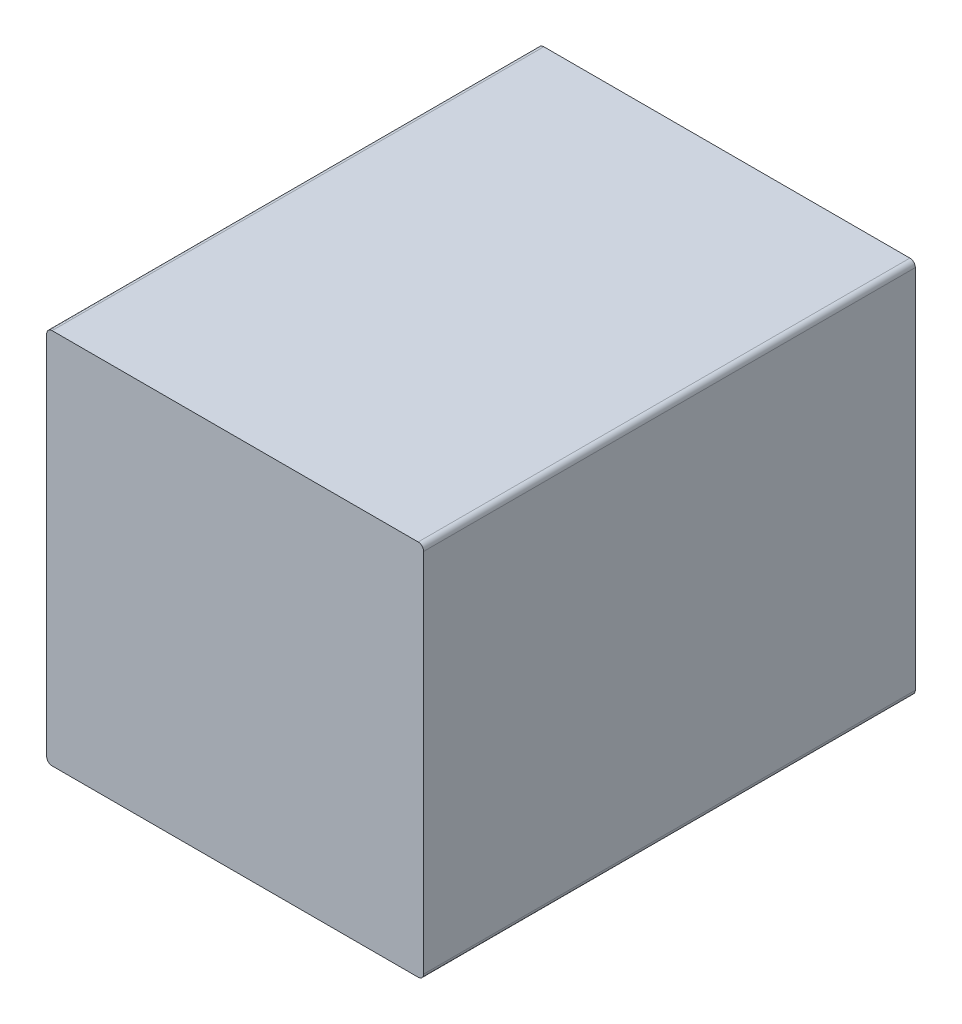
SolidWorks part; units mm, degrees
ref_plane "前视基准面" through (0, 0, 0) normal (0, 0, 1) x (1, 0, 0)
ref_plane "上视基准面" through (0, 0, 0) normal (0, 1, 0) x (1, 0, 0)
ref_plane "右视基准面" through (0, 0, 0) normal (1, 0, 0) x (0, 0, -1)
sketch "草图1" plane through (0, 0, 0) normal (0, 0, 1) x (1, 0, 0)
  line L0 (-16.75, -17.25) -> (16.75, -17.25)
  line L1 (17.25, -16.75) -> (17.25, 16.75)
  line L2 (16.75, 17.25) -> (-16.75, 17.25)
  line L3 (-17.25, 16.75) -> (-17.25, -16.75)
  arc A0 (16.75, -17.25) -> (17.25, -16.75) centre (16.75, -16.75) ccw
  arc A1 (17.25, 16.75) -> (16.75, 17.25) centre (16.75, 16.75) ccw
  arc A2 (-16.75, 17.25) -> (-17.25, 16.75) centre (-16.75, 16.75) ccw
  arc A3 (-17.25, -16.75) -> (-16.75, -17.25) centre (-16.75, -16.75) ccw
  dimension "D1" = 0.5
  dimension "D2" = 17.25
  dimension "D3" = 17.25
  dimension "D4" = 17.25
extrude "连续直线装板扫掠_带0.5余量" add sketch "草图1" along normal blind 45 from offset 11.8
